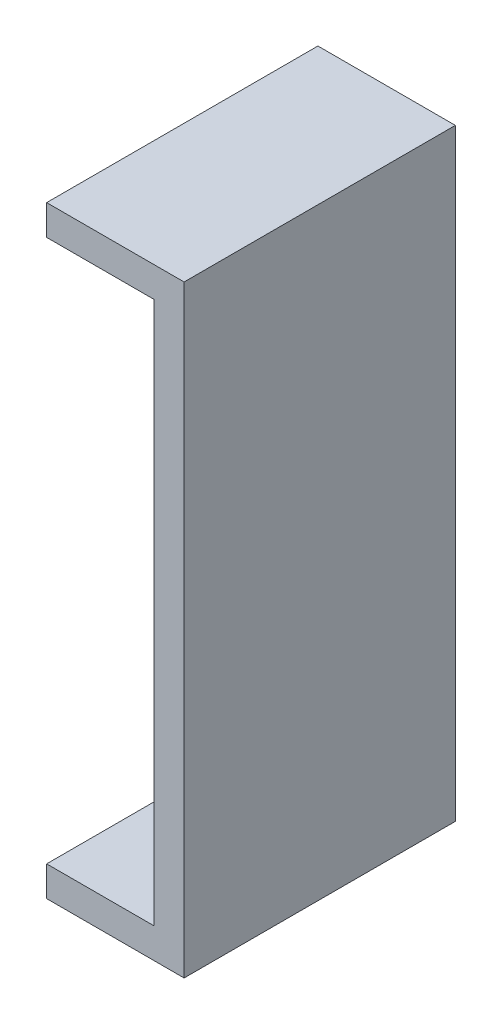
SolidWorks part; units mm, degrees
ref_plane "Front Plane" through (0, 0, 0) normal (1, 0, 0) x (0, 1, 0)
ref_plane "Top Plane" through (0, 0, 0) normal (0, 0, 1) x (0, 1, 0)
ref_plane "Right Plane" through (0, 0, 0) normal (0, 1, 0) x (-1, 0, 0)
sketch "Sketch1" plane through (0, 0, 0) normal (0, 0, 1) x (0, 1, 0)
  line L1 (-50, -37.5) -> (50, -37.5)
  line L2 (-50, -37.5) -> (-50, 37.5)
  line L3 (-50, 37.5) -> (50, 37.5)
  line L4 (50, -37.5) -> (50, 37.5)
  line L5 (-50, -37.5) -> (50, 37.5) construction
  line L6 (-50, 37.5) -> (50, -37.5) construction
  point P0 (0, 0)
extrude "Boss-Extrude1" add sketch "Sketch1" along normal blind 45
sketch "Sketch2" plane through (0, 0, 45) normal (0, 0, 1) x (1, 0, 0)
  line L1 (-32.5, 45) -> (-17.5, 45)
  line L3 (-32.5, 20) -> (-17.5, 20)
  line L4 (-17.5, 45) -> (-17.5, 20)
  line L5 (37.5, 50) -> (-37.5, 50) construction
  line L6 (-32.5, 45) -> (-32.5, 47)
  line L7 (-32.5, 47) -> (-15.5, 47)
  line L8 (-15.5, 47) -> (-15.5, 20)
  line L9 (-15.5, 20) -> (-15.5, 18)
  line L10 (-15.5, 18) -> (-32.5, 18)
  line L11 (-32.5, 18) -> (-32.5, 20)
  line L12 (-32.5, 18) -> (-32.5, -45)
  line L13 (-32.5, -45) -> (32.5, -45)
  line L14 (32.5, -45) -> (32.5, 45)
  line L15 (37.5, -50) -> (37.5, 50) construction
  line L16 (-37.5, -50) -> (37.5, -50) construction
  line L17 (-32.5, 45) -> (-32.5, 20)
  line L18 (32.5, 45) -> (-15.5, 45)
  dimension "D1" = 15
  dimension "D2" = 25
  dimension "D3" = 5
  dimension "D4" = 5
  dimension "D5" = 2
  dimension "D6" = 2
  dimension "D7" = 2
  dimension "D8" = 5
  dimension "D9" = 5
extrude "Cut-Extrude1" cut sketch "Sketch2" against normal through all
sketch "Sketch3" plane through (0, 0, 45) normal (0, 0, 1) x (1, 0, 0)
  line L0 (37.5, 50) -> (-37.5, 50) construction
  line L1 (-15.5, 50) -> (14.6971, 50)
  line L2 (-15.5, 50) -> (-15.5, -50)
  line L3 (-15.5, -50) -> (14.6971, -50)
  line L4 (14.6971, 50) -> (14.6971, -50)
  line L5 (-37.5, -50) -> (37.5, -50) construction
  line L6 (-17.5, 45) -> (-17.5, 20) construction
  dimension "D1" = 2
extrude "Cut-Extrude2" cut sketch "Sketch3" against normal through all contours L4 L3 L2 L1
